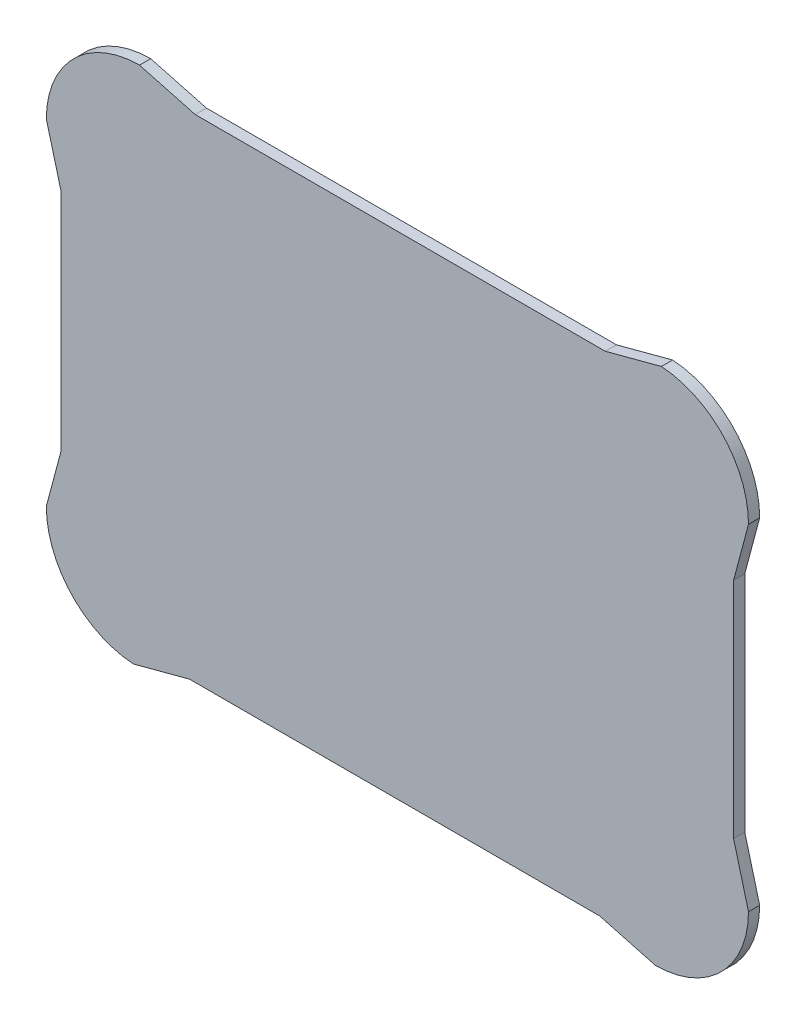
SolidWorks part; units mm, degrees
material "Balsa"
ref_plane "Plan de face" through (0, 0, 0) normal (0, 0, 1) x (1, 0, 0)
ref_plane "Plan de dessus" through (0, 0, 0) normal (0, 1, 0) x (1, 0, 0)
ref_plane "Plan de droite" through (0, 0, 0) normal (1, 0, 0) x (0, 0, -1)
sketch "Esquisse1" plane through (0, 0, 0) normal (0, 0, 1) x (1, 0, 0)
  line L4 (-373.6947, 106.0426) -> (-365.6947, 76.0426)
  line L5 (-365.6947, 76.0426) -> (-365.6947, -43.9574)
  line L6 (-365.6947, -43.9574) -> (-373.6947, -73.9574)
  line L7 (-373.6947, 106.0426) -> (3.0296, 106.0426) construction
  line L8 (-373.6947, -73.9574) -> (3.0296, -73.9574) construction
  line L9 (-365.6947, 76.0426) -> (-365.6947, 106.0426) construction
  line L10 (-365.6947, 106.0426) -> (-365.6947, -73.9574) construction
  line L11 (3.0296, 106.0426) -> (-4.9704, 76.0426)
  line L12 (-4.9704, 76.0426) -> (-4.9704, -43.9574)
  line L13 (-4.9704, -43.9574) -> (3.0296, -73.9574)
  line L14 (-4.9704, 76.0426) -> (-4.9704, 106.0426) construction
  line L15 (-4.9704, 106.0426) -> (-4.9704, -73.9574) construction
  line L16 (-323.697, 156.0345) -> (-326.9694, -123.8593) construction
  line L17 (-43.697, 156.0345) -> (-46.9694, -123.8593) construction
  line L18 (-323.697, 156.0345) -> (-293.7905, 148.0351)
  line L19 (-293.7905, 148.0351) -> (-73.7905, 148.0351)
  line L20 (-73.7905, 148.0351) -> (-43.697, 156.0345)
  line L21 (-293.7905, 148.0351) -> (-323.7905, 148.0351) construction
  line L22 (-323.7905, 148.0351) -> (-43.7905, 148.0351) construction
  line L23 (-326.9694, -123.8593) -> (-296.8759, -115.8599)
  line L24 (-296.8759, -115.8599) -> (-76.8759, -115.8599)
  line L25 (-76.8759, -115.8599) -> (-46.9694, -123.8593)
  line L26 (-296.8759, -115.8599) -> (-326.8759, -115.8599) construction
  line L27 (-326.8759, -115.8599) -> (-46.8759, -115.8599) construction
  arc A0 (3.0296, 106.0426) -> (-43.697, 156.0345) centre (-46.9703, 106.1418) ccw
  arc A1 (-323.697, 156.0345) -> (-373.6947, 106.0426) centre (-323.6947, 106.0345) ccw
  arc A2 (-373.6947, -73.9574) -> (-326.9694, -123.8593) centre (-323.6947, -73.9667) ccw
  arc A3 (3.0296, -73.9574) -> (-46.9694, -123.8593) centre (-46.9703, -73.8593) cw
  dimension "D1" = 50
  dimension "D2" = 50
  dimension "D3" = 50
  dimension "D4" = 50
  dimension "D5" = 280
  dimension "D6" = 180
  dimension "D7" = 180
  dimension "D8" = 8
  dimension "D9" = 120
  dimension "D10" = 8
  dimension "D11" = 30
  dimension "D12" = 120
  dimension "D13" = 8
  dimension "D14" = 8
  dimension "D15" = 8
  dimension "D16" = 220
  dimension "D17" = 8
  dimension "D18" = 30
  dimension "D19" = 30
  dimension "D20" = 30
  dimension "D21" = 30
  dimension "D22" = 8
  dimension "D23" = 8
  dimension "D24" = 220
  dimension "D25" = 30
  dimension "D26" = 30
extrude "Boss.-Extru.1" add sketch "Esquisse1" along normal blind 6
